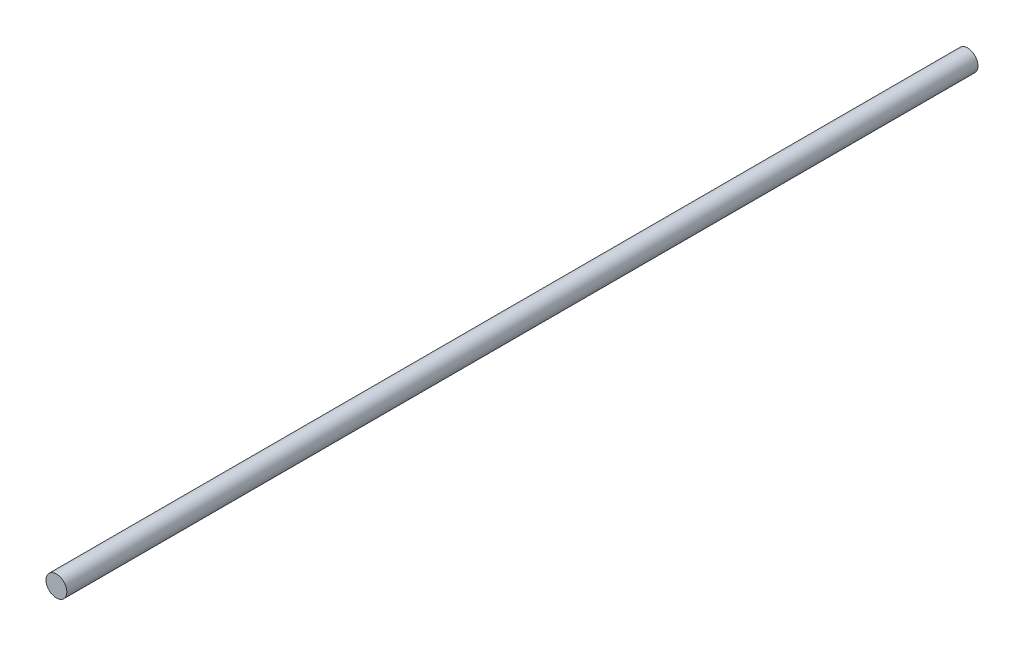
SolidWorks part; units mm, degrees
material "合金钢"
ref_plane "前视基准面" through (0, 0, 0) normal (0, 0, 1) x (1, 0, 0)
ref_plane "上视基准面" through (0, 0, 0) normal (0, 1, 0) x (1, 0, 0)
ref_plane "右视基准面" through (0, 0, 0) normal (1, 0, 0) x (0, 0, -1)
sketch "草图1" plane through (0, 0, 0) normal (0, 0, 1) x (1, 0, 0)
  circle A0 centre (0, 0) radius 4
  dimension "D1" = 8
extrude "凸台-拉伸1" add sketch "草图1" along normal blind 350
sketch "草图2" plane through (0, 0, 350) normal (0, 0, 1) x (1, 0, 0)
  point P0 (0, 0)
sketch "草图3" plane through (0, 0, 0) normal (0, 0, -1) x (-1, 0, 0)
  point P0 (0, 0)
